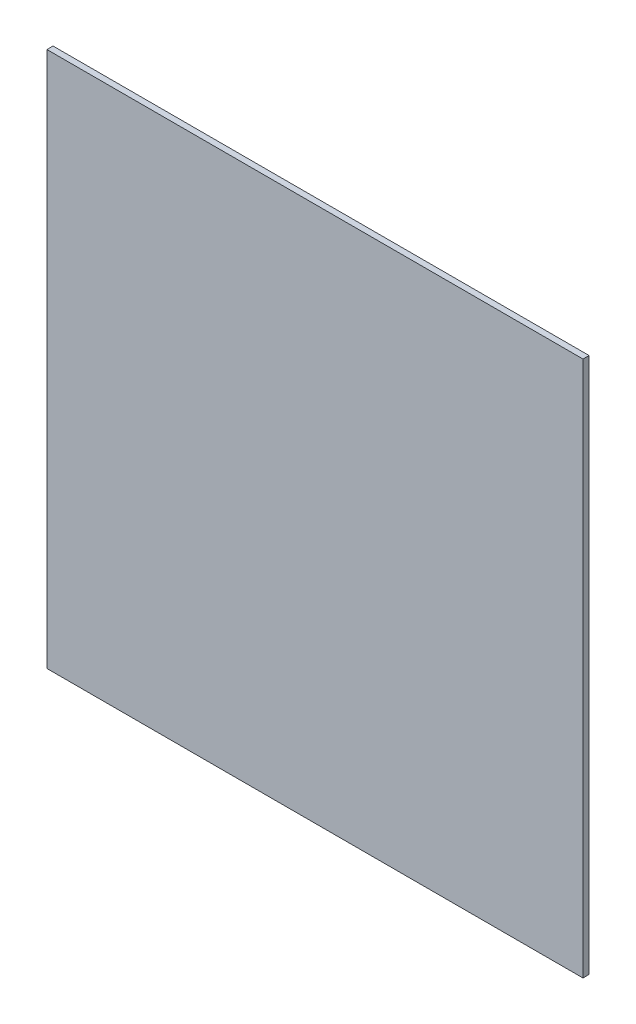
SolidWorks part; units mm, degrees
material "Glass"
ref_plane "Front Plane" through (0, 0, 0) normal (0, 0, 1) x (1, 0, 0)
ref_plane "Top Plane" through (0, 0, 0) normal (0, 1, 0) x (1, 0, 0)
ref_plane "Right Plane" through (0, 0, 0) normal (1, 0, 0) x (0, 0, -1)
sketch "Sketch1" plane through (0, 0, 0) normal (0, 0, 1) x (1, 0, 0)
  line L0 (0, 220) -> (0, -220) construction
  line L1 (-220, 220) -> (220, 220)
  line L2 (-220, 220) -> (-220, -220)
  line L3 (-220, -220) -> (220, -220)
  line L4 (220, 220) -> (220, -220)
  line L5 (-220, 0) -> (220, 0) construction
  dimension "D1" = 440
  dimension "D2" = 440
extrude "Boss-Extrude1" add sketch "Sketch1" along normal blind 5
